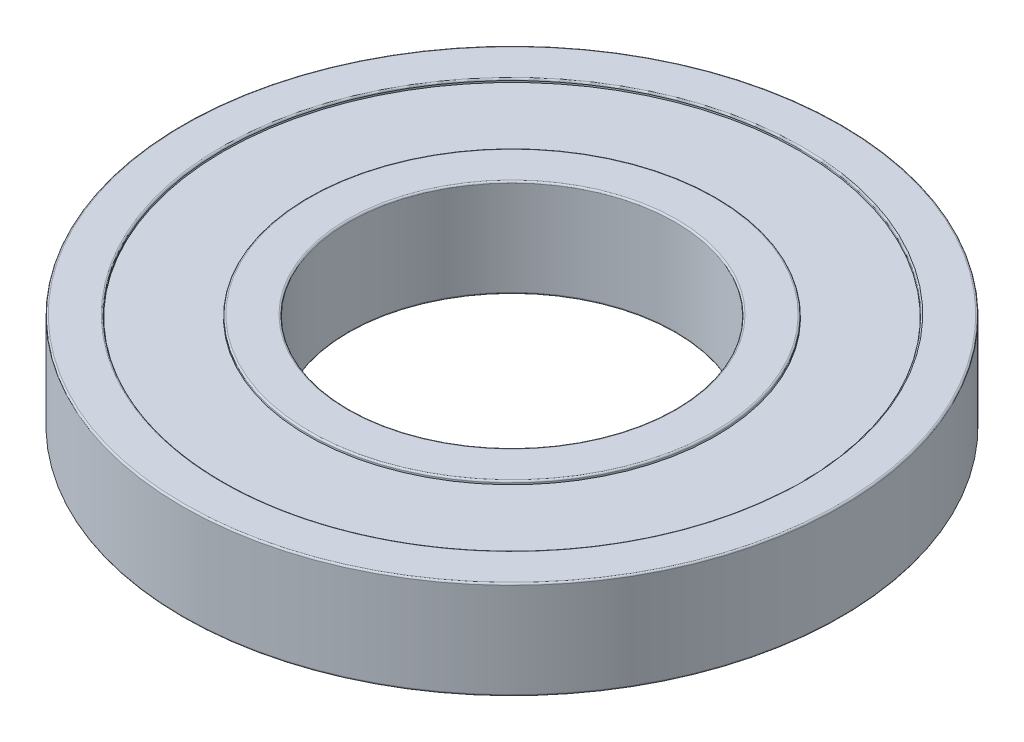
SolidWorks part; units mm, degrees
ref_plane "Front Plane" through (0, 0, 0) normal (0, 0, 1) x (1, 0, 0)
ref_plane "Top Plane" through (0, 0, 0) normal (0, 1, 0) x (1, 0, 0)
ref_plane "Right Plane" through (0, 0, 0) normal (1, 0, 0) x (0, 0, -1)
sketch "Sketch1" plane through (0, 0, 0) normal (0, 0, 1) x (1, 0, 0)
  line L0 (0, 0) -> (0, 2.976) construction
  line L1 (-5, 1.5) -> (-5, -1.5)
  line L2 (-5, -1.5) -> (-6.25, -1.5)
  line L3 (-6.25, -1.5) -> (-6.25, -0.75)
  line L4 (-5, 1.5) -> (-6.25, 1.5)
  line L5 (-6.25, 1.5) -> (-6.25, 0.75)
  line L6 (-7.549, 0) -> (-7.549, -1.9471) construction
  line L7 (-8.8481, 1.5) -> (-8.8481, 0.75)
  line L8 (-10.0981, 1.5) -> (-8.8481, 1.5)
  line L9 (-10.0981, 1.5) -> (-10.0981, -1.5)
  line L10 (-10.0981, -1.5) -> (-8.8481, -1.5)
  line L11 (-8.8481, -1.5) -> (-8.8481, -0.75)
  arc A1 (-6.25, 0.75) -> (-6.25, -0.75) centre (-7.549, 0) cw
  arc A2 (-8.8481, 0.75) -> (-8.8481, -0.75) centre (-7.549, 0) ccw
  dimension "D4" = 1.5
  dimension "D1" = 3
  dimension "D2" = 1.25
  dimension "D3" = 0.75
  dimension "D5" = 5
revolve "Revolve1" add sketch "Sketch1" angle 360 about L0
fillet "Fillet1" radius 0.05 4 edges at (0, -1.5, -10.0981) (0, -1.5, -8.8481) (0, 1.5, -8.8481) (0, 1.5, -10.0981)
fillet "Fillet2" radius 0.05 4 edges at (0, -1.5, -6.25) (0, -1.5, -5) (0, 1.5, -5) (0, 1.5, -6.25)
sketch "Sketch2" plane through (0, 0, 0) normal (0, 0, 1) x (1, 0, 0)
  line L0 (-8.8481, 1.3) -> (-8.8481, 1.4)
  line L1 (-8.8481, 1.5) -> (-8.8481, 0.75) construction
  line L2 (-8.8481, 1.4) -> (-6.25, 1.4)
  line L3 (-6.25, 1.5) -> (-6.25, 0.75) construction
  line L4 (-6.25, 1.4) -> (-6.25, 1.3)
  line L5 (-6.25, 1.3) -> (-8.8481, 1.3)
  line L6 (-7.549, 0) -> (-10.579, 0) construction
  line L7 (-6.25, -1.4) -> (-6.25, -1.3)
  line L8 (-6.25, -1.3) -> (-8.8481, -1.3)
  line L9 (-8.8481, -1.4) -> (-6.25, -1.4)
  line L10 (-8.8481, -1.3) -> (-8.8481, -1.4)
  dimension "D1" = 0.1
  dimension "D2" = 1.3
revolve "Revolve2" add sketch "Sketch2" angle 360 about L0
